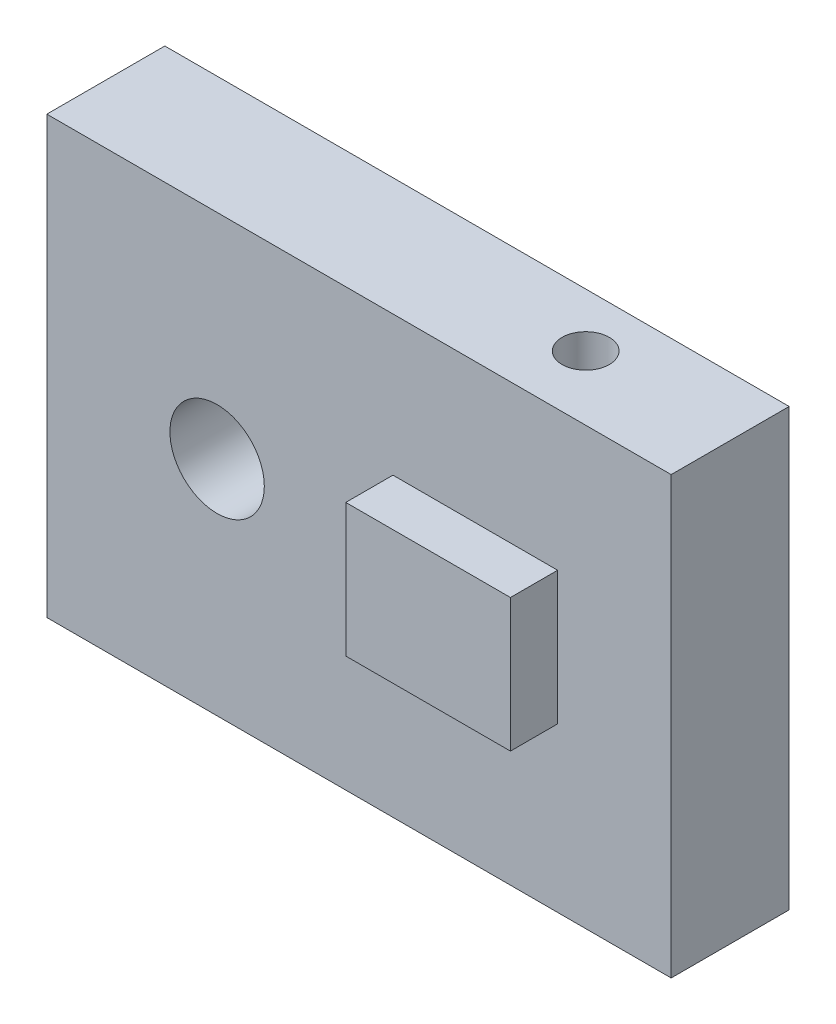
SolidWorks part; units mm, degrees
material "Cast Alloy Steel"
ref_plane "Front Plane" through (0, 0, 0) normal (0, 0, 1) x (1, 0, 0)
ref_plane "Top Plane" through (0, 0, 0) normal (0, 1, 0) x (1, 0, 0)
ref_plane "Right Plane" through (0, 0, 0) normal (1, 0, 0) x (0, 0, -1)
sketch "Sketch1" plane through (0, 0, 0) normal (0, 0, 1) x (1, 0, 0)
  line L1 (-66.138, 46.1842) -> (66.138, 46.1842)
  line L2 (-66.138, 46.1842) -> (-66.138, -46.1842)
  line L3 (-66.138, -46.1842) -> (66.138, -46.1842)
  line L4 (66.138, 46.1842) -> (66.138, -46.1842)
  line L5 (-66.138, 46.1842) -> (66.138, -46.1842) construction
  line L6 (-66.138, -46.1842) -> (66.138, 46.1842) construction
  point P0 (0, 0)
extrude "Boss-Extrude1" add sketch "Sketch1" along normal blind 25
sketch "Sketch4" plane through (0, 0, 25) normal (0, 0, 1) x (1, 0, 0)
  point P0 (-30.06, 0.9363)
hole_wizard "Ø20.0mm Dowel Hole1" positions "Sketch4" profile "Sketch3" hole size "Ø20.0" standard "ISO" end condition through all
sketch "Sketch3" plane through (-30.06, 0.9363, 25) normal (1, 0, 0) x (0, -1, 0)
  line L0 (0, 0) -> (0, 25)
  line L1 (0, 25) -> (10, 25)
  line L2 (10, 25) -> (10, 0)
  line L5 (10, 0) -> (0, 0)
  line L11 (0, -6.35) -> (0, 107.95) construction
  dimension "Thru Hole Dia." = 20
  dimension "Thru Hole Depth" = 25
sketch "Sketch7" plane through (0, 46.1842, 0) normal (0, 1, 0) x (1, 0, 0)
  point P0 (34.3965, -11.3666)
hole_wizard "Ø10.0mm Dowel Hole1" positions "Sketch7" profile "Sketch6" hole size "Ø10.0" standard "ISO" end condition through all
sketch "Sketch6" plane through (34.3965, 46.1842, 11.3666) normal (1, 0, 0) x (0, 0, 1)
  line L0 (0, 0) -> (0, 92.3684)
  line L1 (0, 92.3684) -> (5, 92.3684)
  line L2 (5, 92.3684) -> (5, 0)
  line L5 (5, 0) -> (0, 0)
  line L11 (0, -6.35) -> (0, 107.95) construction
  dimension "Thru Hole Dia." = 10
  dimension "Thru Hole Depth" = 92.3684
sketch "Sketch8" plane through (0, 0, 25) normal (0, 0, 1) x (1, 0, 0)
  line L1 (7.1947, 16.6069) -> (42.084, 16.6069)
  line L2 (7.1947, 16.6069) -> (7.1947, -11.5805)
  line L3 (7.1947, -11.5805) -> (42.084, -11.5805)
  line L4 (42.084, 16.6069) -> (42.084, -11.5805)
  line L5 (7.1947, 16.6069) -> (42.084, -11.5805) construction
  line L6 (7.1947, -11.5805) -> (42.084, 16.6069) construction
  point P0 (24.6393, 2.5132)
extrude "Boss-Extrude2" add sketch "Sketch8" along normal blind 10
